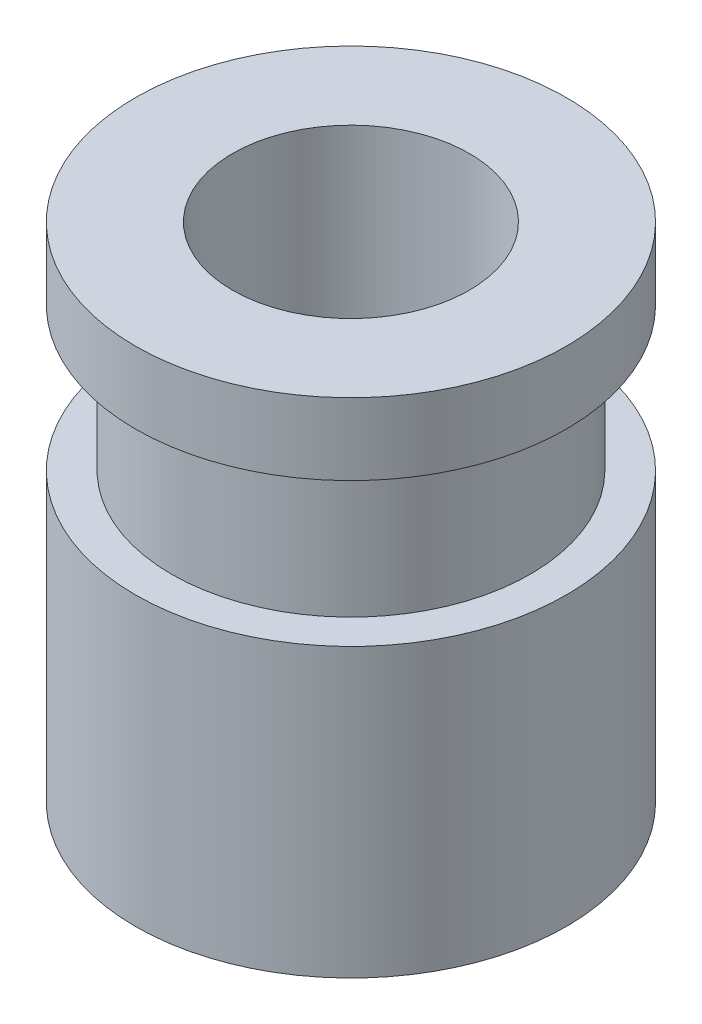
SolidWorks part; units mm, degrees
ref_plane "前视基准面" through (0, 0, 0) normal (0, 0, 1) x (1, 0, 0)
ref_plane "上视基准面" through (0, 0, 0) normal (0, 1, 0) x (1, 0, 0)
ref_plane "右视基准面" through (0, 0, 0) normal (1, 0, 0) x (0, 0, -1)
sketch "草图1" plane through (0, 0, 0) normal (0, 1, 0) x (1, 0, 0)
  circle A0 centre (0, 0) radius 1.65
  circle A1 centre (0, 0) radius 3
  dimension "D1" = 3.3
  dimension "D2" = 6
extrude "凸台-拉伸1" add sketch "草图1" along normal blind 4
sketch "草图2" plane through (0, 4, 0) normal (0, 1, 0) x (1, 0, 0)
  circle A0 centre (0, 0) radius 1.65
  circle A1 centre (0, 0) radius 2.5
  dimension "D1" = 3.3
  dimension "D2" = 5
extrude "凸台-拉伸2" add sketch "草图2" along normal blind 2
sketch "草图3" plane through (0, 6, 0) normal (0, 1, 0) x (1, 0, 0)
  circle A0 centre (0, 0) radius 1.65
  circle A1 centre (0, 0) radius 3
extrude "凸台-拉伸3" add sketch "草图3" along normal blind 1
equation "\"m\"= 2"
